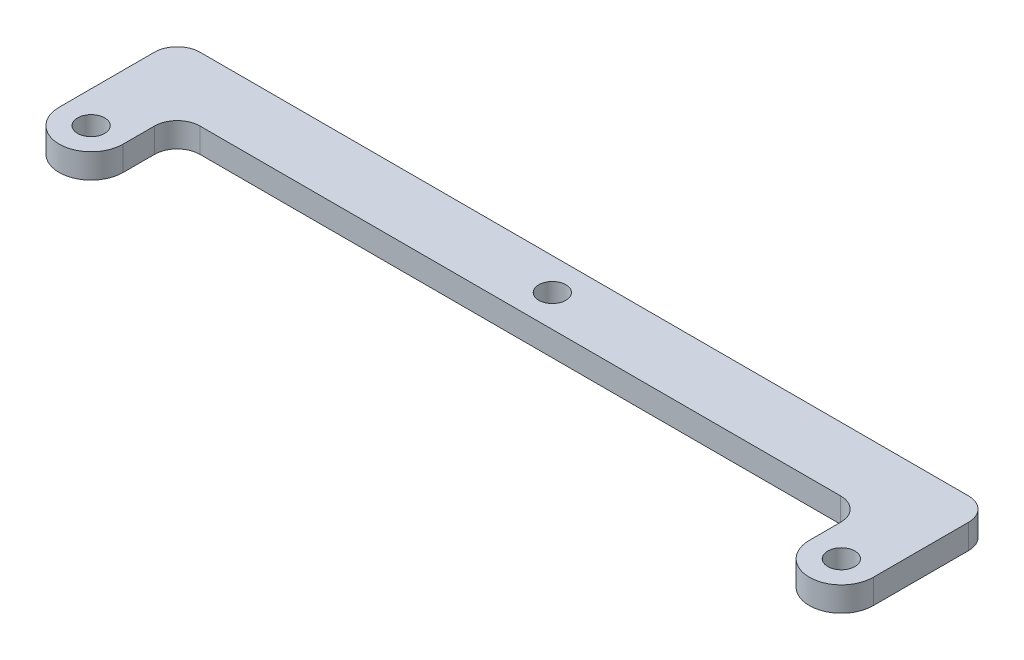
SolidWorks part; units mm, degrees
ref_plane "Front Plane" through (0, 0, 0) normal (0, 0, 1) x (1, 0, 0)
ref_plane "Top Plane" through (0, 0, 0) normal (0, 1, 0) x (1, 0, 0)
ref_plane "Right Plane" through (0, 0, 0) normal (1, 0, 0) x (0, 0, -1)
sketch "Sketch1" plane through (0, 0, 0) normal (0, 1, 0) x (1, 0, 0)
  line L0 (0, 1.1) -> (0, -1.1) construction
  line L1 (-33.1, -7) -> (-33.1, 0.75)
  line L2 (-31.25, 2.6) -> (31.25, 2.6)
  line L3 (-27.9, -7) -> (-27.9, -4.45)
  line L4 (-26.05, -2.6) -> (26.05, -2.6)
  line L5 (27.9, -7) -> (27.9, -4.45)
  line L6 (33.1, -7) -> (33.1, 0.75)
  circle A0 centre (0, 0) radius 1.1
  circle A1 centre (-30.5, -7) radius 1.1
  circle A2 centre (-30.5, -7) radius 2.6
  circle A3 centre (0, 0) radius 2.6
  arc A4 (-27.9, -4.45) -> (-26.05, -2.6) centre (-26.05, -4.45) cw
  arc A5 (-33.1, 0.75) -> (-31.25, 2.6) centre (-31.25, 0.75) cw
  circle A6 centre (30.5, -7) radius 1.1
  circle A7 centre (30.5, -7) radius 2.6
  arc A8 (27.9, -4.45) -> (26.05, -2.6) centre (26.05, -4.45) ccw
  arc A9 (33.1, 0.75) -> (31.25, 2.6) centre (31.25, 0.75) ccw
  point P26 (0, -2.6)
  point P33 (0, 2.6)
  dimension "D1" = 2.2
  dimension "D2" = 2.2
  dimension "D3" = 30.5
  dimension "D4" = 7
  dimension "D6" = 1.85
  dimension "D5" = 1.5
extrude "Boss-Extrude1" add sketch "Sketch1" along normal blind 2 contours A5 L1 A2 L3 A4 L4 A3 L2 | L6 A9 L2 A3 L4 A8 L5 A7 | A3 A0 | A7 A6 | A2 A1
